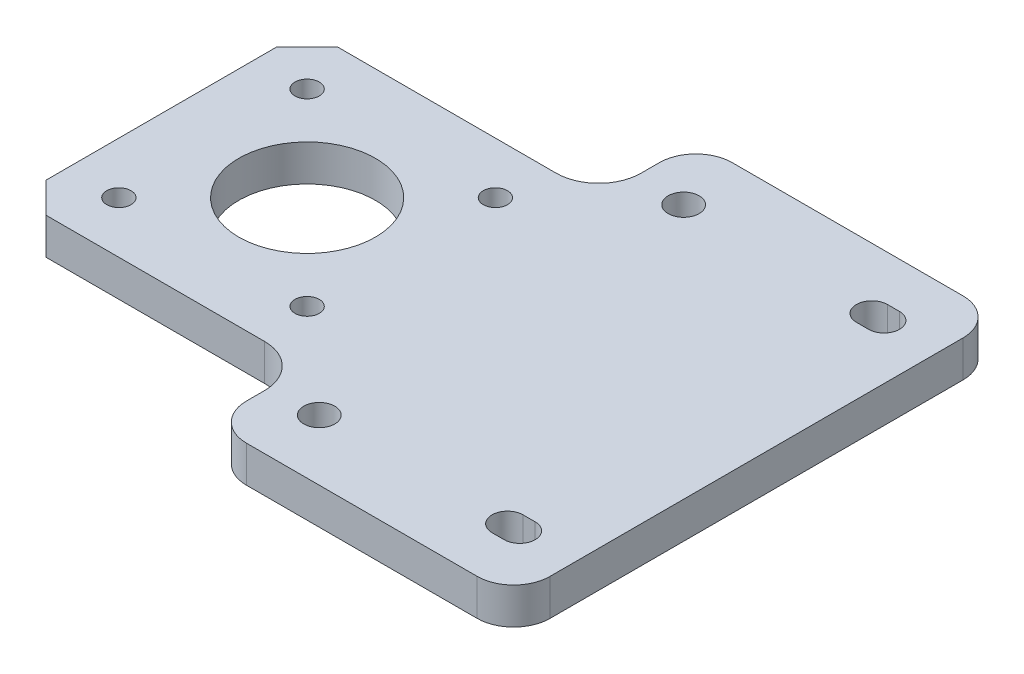
SolidWorks part; units mm, degrees
material "Клен"
ref_plane "Спереди" through (0, 0, 0) normal (0, 0, 1) x (1, 0, 0)
ref_plane "Сверху" through (0, 0, 0) normal (0, 1, 0) x (1, 0, 0)
ref_plane "Справа" through (0, 0, 0) normal (1, 0, 0) x (0, 0, -1)
sketch "Эскиз1" plane through (0, 0, 0) normal (0, 1, 0) x (1, 0, 0)
  line L0 (-56.8562, 0) -> (56.8562, 0) construction
  line L9 (-32, -24) -> (-68, -24)
  line L10 (-19, -40) -> (19, -40)
  line L11 (-25, -34) -> (-25, -31)
  line L12 (-19, 40) -> (19, 40)
  line L13 (25, -34) -> (25, 34)
  line L14 (-25, -40) -> (25, 40) construction
  line L15 (-25, 40) -> (25, -40) construction
  line L20 (-73, -19) -> (-73, 19)
  line L21 (-32, 24) -> (-68, 24)
  line L22 (-25, 31) -> (-25, 34)
  line L23 (-68, -24) -> (-73, -19)
  line L24 (-68, 24) -> (-73, 19)
  line L25 (-73, -24) -> (-25, 24) construction
  line L26 (-25, -24) -> (-72.5248, 23.5248) construction
  line L27 (-49, -29.3961) -> (-49, 34.1878) construction
  arc A4 (19, 40) -> (25, 34) centre (19, 34) cw
  arc A5 (19, -40) -> (25, -34) centre (19, -34) ccw
  arc A6 (-19, -40) -> (-25, -34) centre (-19, -34) cw
  arc A7 (-25, 34) -> (-19, 40) centre (-19, 34) cw
  circle A8 centre (-49, 0) radius 11.25
  circle A9 centre (-64.5, 15.5) radius 2
  circle A10 centre (-64.5, -15.5) radius 2
  circle A11 centre (-33.5, 15.5) radius 2
  circle A12 centre (-33.5, -15.5) radius 2
  arc A13 (-25, -31) -> (-32, -24) centre (-32, -31) ccw
  arc A14 (-32, 24) -> (-25, 31) centre (-32, 31) ccw
  point P0 (0, 0)
  point P22 (-73, -24)
  point P24 (-73, 24)
  point P25 (-75, 0)
  point P32 (-49, 0)
  point P34 (-49.8171, 0.0009)
  point P35 (-49, 0)
  point P36 (-24.7404, 0.0009)
  point P37 (-49, 0)
  point P39 (-49, 0)
  point P52 (0, 0)
  point P56 (-25, 32.5)
  dimension "D1" = 6
  dimension "D6" = 22.5
  dimension "D7" = 4
  dimension "D13" = 7
  dimension "D14" = 7
  dimension "D2" = 80
  dimension "D3" = 50
  dimension "D4" = 48
  dimension "D10" = 15.5
  dimension "D11" = 15.5
  dimension "D12" = 15.5
  dimension "D5" = 48
extrude "Бобышка-Вытянуть1" add sketch "Эскиз1" along normal blind 6
sketch "Эскиз2" plane through (0, 0, 0) normal (0, -1, 0) x (1, 0, 0)
  line L0 (0, -37.0349) -> (0, 29.2907) construction
  line L1 (16, -30) -> (14, -30) construction
  line L2 (16, -32.55) -> (14, -32.55)
  line L3 (16, -27.45) -> (14, -27.45)
  line L6 (-46.1924, 0) -> (55.6646, 0) construction
  line L7 (16, 30) -> (14, 30) construction
  line L8 (16, 32.55) -> (14, 32.55)
  line L9 (16, 27.45) -> (14, 27.45)
  line L10 (-25, 31) -> (-25, 34) construction
  line L11 (19, -40) -> (-19, -40) construction
  circle A0 centre (-17, -30) radius 2.55
  arc A1 (16, -32.55) -> (16, -27.45) centre (16, -30) ccw
  arc A2 (14, -27.45) -> (14, -32.55) centre (14, -30) ccw
  arc A3 (16, 32.55) -> (16, 27.45) centre (16, 30) cw
  arc A4 (14, 27.45) -> (14, 32.55) centre (14, 30) cw
  circle A5 centre (-17, 30) radius 2.55
  point P7 (15, -30)
  point P12 (15, -32.55)
  point P21 (15, 30)
  dimension "D1" = 5.1
  dimension "D2" = 5.1
  dimension "D3" = 2
  dimension "D4" = 33
  dimension "D5" = 8
  dimension "D6" = 10
extrude "Вырез-Вытянуть1" cut sketch "Эскиз2" against normal through all
equation "\"D2@Эскиз2\"=\"D1@Эскиз2\""
equation "\"D5@Эскиз1\"=\"D4@Эскиз1\""
